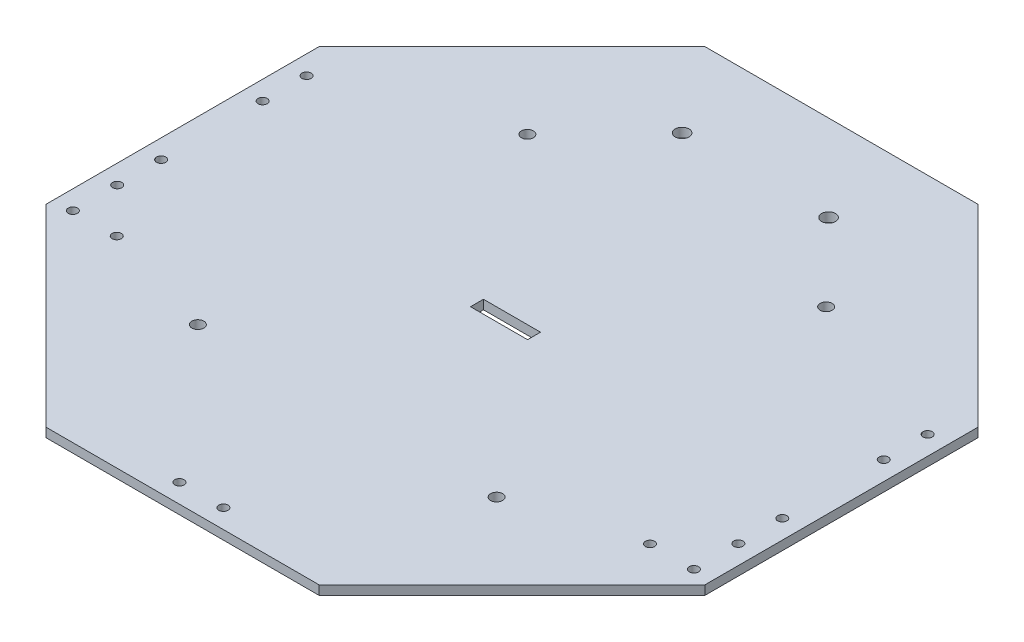
SolidWorks part; units mm, degrees
ref_plane "Front Plane" through (0, 0, 0) normal (0, 0, 1) x (1, 0, 0)
ref_plane "Top Plane" through (0, 0, 0) normal (0, 1, 0) x (1, 0, 0)
ref_plane "Right Plane" through (0, 0, 0) normal (1, 0, 0) x (0, 0, -1)
sketch "Sketch1" plane through (0, 0, 0) normal (0, 1, 0) x (1, 0, 0)
  line L1 (0, 139.7) -> (152.4, 139.7) construction
  line L2 (152.4, 139.7) -> (152.4, 0) construction
  line L4 (76.2, 139.7) -> (76.2, 0) construction
  line L8 (24.384, 0) -> (24.384, 12.7) construction
  line L9 (1.3179, 69.85) -> (152.4, 69.85) construction
  line L10 (0, 139.7) -> (0, 0) construction
  line L11 (0, 0) -> (152.4, 0) construction
  line L12 (24.384, 12.7) -> (0, 12.7) construction
  line L13 (128.016, 0) -> (128.016, 12.7) construction
  line L14 (128.016, 12.7) -> (152.4, 12.7) construction
  line L15 (128.016, 127) -> (152.4, 127) construction
  line L16 (128.016, 139.7) -> (128.016, 127) construction
  line L17 (24.384, 139.7) -> (24.384, 127) construction
  line L18 (24.384, 127) -> (0, 127) construction
  line L19 (76.2, -44.45) -> (76.2, -30.45) construction
  line L20 (-38.1, 69.85) -> (190.5, 69.85) construction
  line L21 (28.8554, 184.15) -> (123.5446, 184.15)
  line L22 (190.5, 22.5054) -> (190.5, 117.1946)
  line L23 (28.8554, -44.45) -> (123.5446, -44.45)
  line L24 (-38.1, 22.5054) -> (-38.1, 117.1946)
  line L29 (28.8554, 184.15) -> (-24.1, 131.1946)
  line L30 (123.5446, 184.15) -> (176.5, 131.1946)
  line L31 (-38.1, 22.5054) -> (-30.1, 14.5054)
  line L32 (190.5, 22.5054) -> (182.5, 14.5054)
  line L33 (-38.1, 69.85) -> (-24.1, 69.85) construction
  line L34 (-24.1, 27.94) -> (-24.1, 111.76) construction
  line L35 (-30.1, 125.1946) -> (-38.1, 117.1946)
  line L40 (-24.1, 8.5054) -> (14.8554, -30.45)
  line L45 (-4.6223, -10.9723) -> (157.0223, 150.6723) construction
  line L46 (137.5446, -30.45) -> (131.5446, -36.45)
  line L47 (76.2, -44.45) -> (76.2, -30.45) construction
  line L55 (190.5, 69.85) -> (176.5, 69.85) construction
  line L62 (20.8554, -36.45) -> (28.8554, -44.45)
  line L63 (131.5446, -36.45) -> (123.5446, -44.45)
  line L64 (176.5, 8.5054) -> (137.5446, -30.45)
  line L65 (182.5, 125.1946) -> (190.5, 117.1946)
  line L66 (14.8554, -30.45) -> (20.8554, -36.45)
  line L67 (76.2, 0) -> (76.2, 184.15) construction
  line L68 (182.5, 125.1946) -> (176.5, 131.1946)
  line L69 (182.5, 14.5054) -> (176.5, 8.5054)
  line L70 (-24.1, 131.1946) -> (-30.1, 125.1946)
  line L71 (-30.1, 14.5054) -> (-24.1, 8.5054)
  circle A0 centre (24.384, 12.7) radius 2.0828
  circle A1 centre (128.016, 12.7) radius 2.0828
  circle A2 centre (128.016, 127) radius 2.0828
  circle A3 centre (24.384, 127) radius 2.0828
  point P28 (76.2, 69.85)
  point P31 (76.2, 69.85)
  point P34 (76.2, 184.15)
  point P37 (190.5, 69.85)
  point P40 (76.2, -44.45)
  point P46 (-24.1, 69.85)
  point P55 (76.2, 69.85)
  dimension "D3" = 24.384
  dimension "D1" = 139.7
  dimension "D2" = 152.4
  dimension "D4" = 12.7
  dimension "D5" = 94.6892
  dimension "D6" = 228.6
extrude "Boss-Extrude1" add sketch "Sketch1" along normal blind 3.175
sketch "Sketch2" plane through (0, 3.175, 0) normal (0, 1, 0) x (1, 0, 0)
  line L21 (-31.5214, 106.3131) -> (-31.5214, 91.0731) construction
  line L22 (-31.5214, 40.6396) -> (-31.5214, 55.8796) construction
  line L23 (-31.5214, 25.2303) -> (-16.2814, 25.2303) construction
  line L24 (83.82, -37.8714) -> (68.58, -37.8714) construction
  line L25 (76.2, -44.45) -> (76.2, 179.1379) construction
  line L26 (28.8554, -44.45) -> (123.5446, -44.45) construction
  line L35 (183.9214, 25.2303) -> (168.6814, 25.2303) construction
  line L36 (183.9214, 40.6396) -> (183.9214, 55.8796) construction
  line L37 (183.9214, 106.3131) -> (183.9214, 91.0731) construction
  point P19 (76.2, -37.8714)
hole_wizard "M3 Clearance Hole1" positions "Sketch3" profile "Sketch4" hole size "M3" standard "ANSI Metric" end condition through all
sketch "Sketch3" plane through (0, 3.175, 0) normal (0, 1, 0) x (1, 0, 0)
  point P0 (-31.5214, 106.3131)
  point P3 (-31.5214, 91.0731)
  point P6 (-31.5214, 55.8796)
  point P9 (-31.5214, 40.6396)
  point P12 (-31.5214, 25.2303)
  point P15 (-16.2814, 25.2303)
  point P18 (68.58, -37.8714)
  point P21 (83.82, -37.8714)
  point P24 (183.9214, 25.2303)
  point P27 (168.6814, 25.2303)
  point P30 (183.9214, 40.6396)
  point P33 (183.9214, 55.8796)
  point P36 (183.9214, 91.0731)
  point P39 (183.9214, 106.3131)
sketch "Sketch4" plane through (-31.5214, 3.175, -106.3131) normal (1, 0, 0) x (0, 0, 1)
  line L0 (0, 0) -> (0, 3.175)
  line L1 (0, 3.175) -> (1.6, 3.175)
  line L2 (1.6, 3.175) -> (1.6, 0)
  line L5 (1.6, 0) -> (0, 0)
  line L11 (0, -6.35) -> (0, 107.95) construction
  dimension "Thru Hole Dia." = 3.2
  dimension "Thru Hole Depth" = 3.175
sketch "Sketch5" plane through (0, 3.175, 0) normal (0, 1, 0) x (1, 0, 0)
  line L0 (-38.1, 69.85) -> (190.5, 69.85) construction
  line L3 (86.1, 69.85) -> (66.3, 69.85)
  line L4 (86.1, 69.85) -> (86.1, 65.35)
  line L5 (86.1, 65.35) -> (66.3, 65.35)
  line L6 (66.3, 69.85) -> (66.3, 65.35)
  line L7 (86.1, 72.1) -> (66.3, 67.6) construction
  line L8 (86.1, 67.6) -> (66.3, 72.1) construction
  line L9 (-38.1, 117.1946) -> (-38.1, 22.5054) construction
  line L10 (190.5, 22.5054) -> (190.5, 117.1946) construction
  dimension "D1" = 19.8
  dimension "D2" = 4.5
extrude "Cut-Extrude1" cut sketch "Sketch5" against normal through all
sketch "Sketch6" plane through (0, 3.175, 0) normal (0, 1, 0) x (1, 0, 0)
  line L0 (190.5, 69.85) -> (-38.1, 69.85) construction
  line L1 (190.5, 22.5054) -> (190.5, 117.1946) construction
  line L2 (-38.1, 117.1946) -> (-38.1, 22.5054) construction
sketch "Sketch7" plane through (0, 3.175, 0) normal (0, 1, 0) x (1, 0, 0)
  line L0 (76.2, 154.2636) -> (50.8, 154.2636) construction
  line L1 (76.2, -44.45) -> (76.2, 179.1379) construction
  line L2 (76.2, 179.1379) -> (76.2, 133.7812) construction
  circle A0 centre (50.8, 154.2636) radius 2.413
  circle A1 centre (101.6, 154.2636) radius 2.413
extrude "Cut-Extrude2" cut sketch "Sketch7" against normal through all
